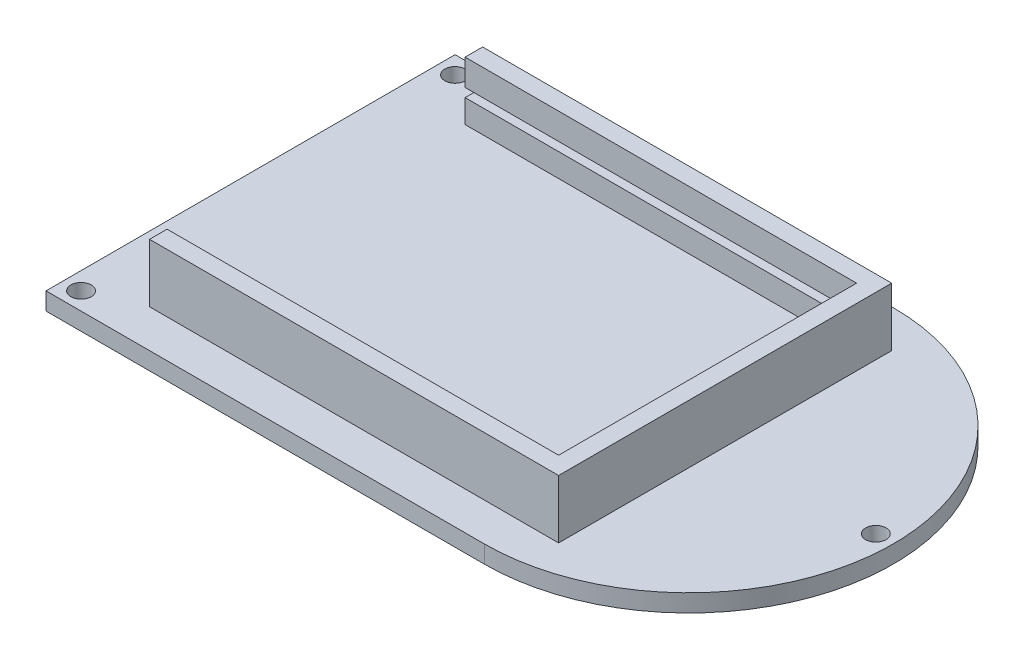
SolidWorks part; units mm, degrees
ref_plane "Alzado" through (0, 0, 0) normal (0, 0, 1) x (1, 0, 0)
ref_plane "Planta" through (0, 0, 0) normal (0, 1, 0) x (1, 0, 0)
ref_plane "Vista lateral" through (0, 0, 0) normal (1, 0, 0) x (0, 0, -1)
sketch "Croquis1" plane through (0, 0, 0) normal (0, 1, 0) x (1, 0, 0)
  line L1 (0, 35) -> (-75, 35)
  line L2 (0, -35) -> (-75, -35)
  line L3 (-75, 35) -> (-75, -35)
  arc A0 (0, -35) -> (0, 35) centre (0, 0) ccw
  circle A1 centre (-72, 32) radius 1.75
  circle A2 centre (-72, -32) radius 1.75
  circle A3 centre (32, 0) radius 1.75
  dimension "D1" = 75
  dimension "D2" = 3
  dimension "D6" = 32
  dimension "D3" = 3
  dimension "D4" = 3
  dimension "D5" = 3
extrude "Saliente-Extruir1" add sketch "Croquis1" along normal blind 3
sketch "Croquis3" plane through (0, 3, 0) normal (0, 1, 0) x (1, 0, 0)
  line L0 (0, 35) -> (-75, 35) construction
  line L1 (6.2205, 28.5) -> (-63.7795, 28.5)
  line L2 (6.2205, 28.5) -> (6.2205, -28.5)
  line L3 (6.2205, -28.5) -> (-63.7795, -28.5)
  line L4 (-63.7795, 28.5) -> (-63.7795, 25.5)
  line L5 (6.2205, 28.5) -> (-63.7795, -28.5) construction
  line L6 (6.2205, -28.5) -> (-63.7795, 28.5) construction
  line L7 (-63.7795, -25.5) -> (-63.7795, -28.5)
  line L8 (-63.7795, 25.5) -> (3.2205, 25.5)
  line L10 (-63.7795, -25.5) -> (3.2205, -25.5)
  line L11 (3.2205, 25.5) -> (3.2205, -25.5)
  point P0 (-28.7795, 0)
  dimension "D1" = 35
  dimension "D2" = 70
  dimension "D3" = 57
  dimension "D4" = 3
  dimension "D5" = 3
  dimension "D6" = 3
extrude "Saliente-Extruir3" add sketch "Croquis3" along normal blind 10
ref_plane "Plano18" through (0, 7, 0) normal (0, 1, 0) x (1, 0, 0)
sketch "Croquis4" plane through (0, 7, 0) normal (0, 1, 0) x (1, 0, 0)
  line L0 (-63.7795, 25.5) -> (3.2205, 25.5) construction
  line L1 (-65.9615, 27) -> (4.7205, 27)
  line L2 (-65.9615, 27) -> (-65.9615, -27)
  line L3 (-65.9615, -27) -> (4.7205, -27)
  line L4 (4.7205, 27) -> (4.7205, -27)
  line L5 (3.2205, 25.5) -> (3.2205, -25.5) construction
  line L6 (3.2205, -25.5) -> (-63.7795, -25.5) construction
  dimension "D1" = 1.5
  dimension "D2" = 1.5
  dimension "D3" = 1.5
extrude "Cortar-Extruir1" cut sketch "Croquis4" along normal blind 1.5
